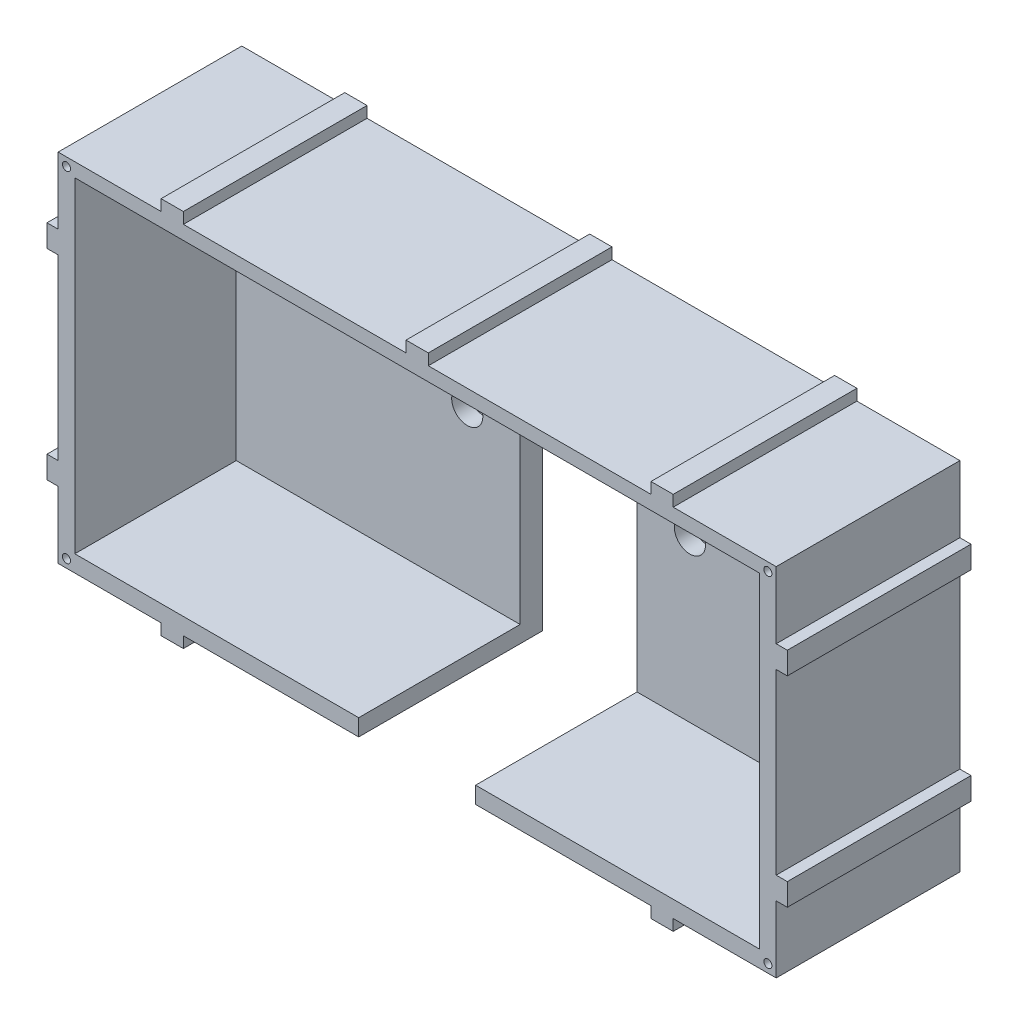
SolidWorks part; units mm, degrees
ref_plane "前视基准面" through (0, 0, 0) normal (0, 0, 1) x (1, 0, 0)
ref_plane "上视基准面" through (0, 0, 0) normal (0, 1, 0) x (1, 0, 0)
ref_plane "右视基准面" through (0, 0, 0) normal (1, 0, 0) x (0, 0, -1)
sketch "Model" plane through (0, 0, 0) normal (0, 0, 1) x (1, 0, 0)
  line L0 (257.5557, 185.1803) -> (276.0557, 185.1803)
  line L1 (386.5557, 121.1803) -> (368.0557, 121.1803)
  line L2 (257.5557, 121.1803) -> (257.5557, 133.1803)
  line L3 (386.5557, 185.1803) -> (386.5557, 173.1803)
  line L4 (324.0557, 185.1803) -> (324.0557, 187.1803)
  line L5 (324.0557, 187.1803) -> (320.0557, 187.1803)
  line L6 (320.0557, 187.1803) -> (320.0557, 185.1803)
  line L7 (280.0557, 185.1803) -> (280.0557, 187.1803)
  line L8 (280.0557, 187.1803) -> (276.0557, 187.1803)
  line L9 (276.0557, 187.1803) -> (276.0557, 185.1803)
  line L10 (368.0557, 185.1803) -> (368.0557, 187.1803)
  line L11 (368.0557, 187.1803) -> (364.0557, 187.1803)
  line L12 (364.0557, 187.1803) -> (364.0557, 185.1803)
  line L13 (280.0557, 121.1803) -> (280.0557, 119.1803)
  line L14 (280.0557, 119.1803) -> (276.0557, 119.1803)
  line L15 (276.0557, 119.1803) -> (276.0557, 121.1803)
  line L16 (368.0557, 121.1803) -> (368.0557, 119.1803)
  line L17 (368.0557, 119.1803) -> (364.0557, 119.1803)
  line L18 (364.0557, 119.1803) -> (364.0557, 121.1803)
  line L19 (257.5557, 173.1803) -> (255.5557, 173.1803)
  line L20 (255.5557, 173.1803) -> (255.5557, 169.1803)
  line L21 (255.5557, 169.1803) -> (257.5557, 169.1803)
  line L22 (257.5557, 133.1803) -> (255.5557, 133.1803)
  line L23 (255.5557, 133.1803) -> (255.5557, 137.1803)
  line L24 (255.5557, 137.1803) -> (257.5557, 137.1803)
  line L25 (386.5557, 173.1803) -> (388.5557, 173.1803)
  line L26 (388.5557, 173.1803) -> (388.5557, 169.1803)
  line L27 (388.5557, 169.1803) -> (386.5557, 169.1803)
  line L28 (386.5557, 133.1803) -> (388.5557, 133.1803)
  line L29 (388.5557, 133.1803) -> (388.5557, 137.1803)
  line L30 (388.5557, 137.1803) -> (386.5557, 137.1803)
  line L31 (257.5557, 173.1803) -> (257.5557, 185.1803)
  line L32 (257.5557, 137.1803) -> (257.5557, 169.1803)
  line L33 (276.0557, 121.1803) -> (257.5557, 121.1803)
  line L34 (364.0557, 121.1803) -> (332.5557, 121.1803)
  line L35 (386.5557, 133.1803) -> (386.5557, 121.1803)
  line L36 (386.5557, 169.1803) -> (386.5557, 137.1803)
  line L37 (368.0557, 185.1803) -> (386.5557, 185.1803)
  line L38 (332.5557, 121.1803) -> (332.5557, 182.6803)
  line L39 (311.5557, 121.1803) -> (311.5557, 182.6803)
  line L40 (311.5557, 182.6803) -> (332.5557, 182.6803)
  line L41 (311.5557, 121.1803) -> (280.0557, 121.1803)
  line L42 (280.0557, 185.1803) -> (320.0557, 185.1803)
  line L43 (324.0557, 185.1803) -> (364.0557, 185.1803)
  line L44 (322.0557, 182.6803) -> (322.0557, 130.4829) construction
  circle A0 centre (342.0557, 153.1803) radius 1.6
  circle A1 centre (302.0557, 153.1803) radius 1.6
extrude "凸台-拉伸1" add sketch "Model" along normal blind 4
sketch "草图2" plane through (0, 0, 4) normal (0, 0, 1) x (1, 0, 0)
  circle A0 centre (302.0557, 153.1803) radius 2.8
  circle A1 centre (342.0557, 153.1803) radius 2.8
  circle A2 centre (342.0557, 153.1803) radius 1.6 construction
  circle A3 centre (302.0557, 153.1803) radius 1.6 construction
  circle A4 centre (342.0557, 153.1803) radius 1.6
  circle A5 centre (302.0557, 153.1803) radius 1.6
  dimension "D1" = 5.6
  dimension "D2" = 5.6
extrude "切除-拉伸1" cut sketch "草图2" against normal blind 3
sketch "草图3" plane through (0, 0, 4) normal (0, 0, 1) x (1, 0, 0)
  line L0 (260.5557, 182.6803) -> (260.5557, 124.1803)
  line L1 (260.5557, 124.1803) -> (311.5557, 124.1803)
  line L2 (383.5557, 124.1803) -> (383.5557, 182.6803)
  line L4 (332.5557, 124.1803) -> (383.5557, 124.1803)
  line L5 (260.5557, 182.6803) -> (383.5557, 182.6803)
  line L44 (257.5557, 185.1803) -> (257.5557, 173.1803)
  line L45 (257.5557, 173.1803) -> (255.5557, 173.1803)
  line L46 (255.5557, 173.1803) -> (255.5557, 169.1803)
  line L47 (255.5557, 169.1803) -> (257.5557, 169.1803)
  line L48 (257.5557, 169.1803) -> (257.5557, 137.1803)
  line L49 (257.5557, 137.1803) -> (255.5557, 137.1803)
  line L50 (255.5557, 137.1803) -> (255.5557, 133.1803)
  line L51 (255.5557, 133.1803) -> (257.5557, 133.1803)
  line L52 (257.5557, 133.1803) -> (257.5557, 121.1803)
  line L53 (257.5557, 121.1803) -> (276.0557, 121.1803)
  line L54 (276.0557, 121.1803) -> (276.0557, 119.1803)
  line L55 (276.0557, 119.1803) -> (280.0557, 119.1803)
  line L56 (280.0557, 119.1803) -> (280.0557, 121.1803)
  line L57 (280.0557, 121.1803) -> (311.5557, 121.1803)
  line L58 (311.5557, 121.1803) -> (311.5557, 182.6803)
  line L59 (311.5557, 182.6803) -> (332.5557, 182.6803)
  line L60 (332.5557, 182.6803) -> (332.5557, 121.1803)
  line L61 (332.5557, 121.1803) -> (364.0557, 121.1803)
  line L62 (364.0557, 121.1803) -> (364.0557, 119.1803)
  line L63 (364.0557, 119.1803) -> (368.0557, 119.1803)
  line L64 (368.0557, 119.1803) -> (368.0557, 121.1803)
  line L65 (368.0557, 121.1803) -> (386.5557, 121.1803)
  line L66 (386.5557, 121.1803) -> (386.5557, 133.1803)
  line L67 (386.5557, 133.1803) -> (388.5557, 133.1803)
  line L68 (388.5557, 133.1803) -> (388.5557, 137.1803)
  line L69 (388.5557, 137.1803) -> (386.5557, 137.1803)
  line L70 (386.5557, 137.1803) -> (386.5557, 169.1803)
  line L71 (386.5557, 169.1803) -> (388.5557, 169.1803)
  line L72 (388.5557, 169.1803) -> (388.5557, 173.1803)
  line L73 (388.5557, 173.1803) -> (386.5557, 173.1803)
  line L74 (386.5557, 173.1803) -> (386.5557, 185.1803)
  line L75 (386.5557, 185.1803) -> (368.0557, 185.1803)
  line L76 (368.0557, 185.1803) -> (368.0557, 187.1803)
  line L77 (368.0557, 187.1803) -> (364.0557, 187.1803)
  line L78 (364.0557, 187.1803) -> (364.0557, 185.1803)
  line L79 (364.0557, 185.1803) -> (324.0557, 185.1803)
  line L80 (324.0557, 185.1803) -> (324.0557, 187.1803)
  line L81 (324.0557, 187.1803) -> (320.0557, 187.1803)
  line L82 (320.0557, 187.1803) -> (320.0557, 185.1803)
  line L83 (320.0557, 185.1803) -> (280.0557, 185.1803)
  line L84 (280.0557, 185.1803) -> (280.0557, 187.1803)
  line L85 (280.0557, 187.1803) -> (276.0557, 187.1803)
  line L86 (276.0557, 187.1803) -> (276.0557, 185.1803)
  line L87 (276.0557, 185.1803) -> (257.5557, 185.1803)
  line L88 (257.5557, 185.1803) -> (257.5557, 173.1803)
  line L89 (257.5557, 173.1803) -> (255.5557, 173.1803)
  line L90 (255.5557, 173.1803) -> (255.5557, 169.1803)
  line L91 (255.5557, 169.1803) -> (257.5557, 169.1803)
  line L92 (257.5557, 169.1803) -> (257.5557, 137.1803)
  line L93 (257.5557, 137.1803) -> (255.5557, 137.1803)
  line L94 (255.5557, 137.1803) -> (255.5557, 133.1803)
  line L95 (255.5557, 133.1803) -> (257.5557, 133.1803)
  line L96 (257.5557, 133.1803) -> (257.5557, 121.1803)
  line L97 (257.5557, 121.1803) -> (276.0557, 121.1803)
  line L98 (276.0557, 121.1803) -> (276.0557, 119.1803)
  line L99 (276.0557, 119.1803) -> (280.0557, 119.1803)
  line L100 (280.0557, 119.1803) -> (280.0557, 121.1803)
  line L101 (280.0557, 121.1803) -> (311.5557, 121.1803)
  line L102 (311.5557, 121.1803) -> (311.5557, 124.1803)
  line L104 (332.5557, 124.1803) -> (332.5557, 121.1803)
  line L105 (332.5557, 121.1803) -> (364.0557, 121.1803)
  line L106 (364.0557, 121.1803) -> (364.0557, 119.1803)
  line L107 (364.0557, 119.1803) -> (368.0557, 119.1803)
  line L108 (368.0557, 119.1803) -> (368.0557, 121.1803)
  line L109 (368.0557, 121.1803) -> (386.5557, 121.1803)
  line L110 (386.5557, 121.1803) -> (386.5557, 133.1803)
  line L111 (386.5557, 133.1803) -> (388.5557, 133.1803)
  line L112 (388.5557, 133.1803) -> (388.5557, 137.1803)
  line L113 (388.5557, 137.1803) -> (386.5557, 137.1803)
  line L114 (386.5557, 137.1803) -> (386.5557, 169.1803)
  line L115 (386.5557, 169.1803) -> (388.5557, 169.1803)
  line L116 (388.5557, 169.1803) -> (388.5557, 173.1803)
  line L117 (388.5557, 173.1803) -> (386.5557, 173.1803)
  line L118 (386.5557, 173.1803) -> (386.5557, 185.1803)
  line L119 (386.5557, 185.1803) -> (368.0557, 185.1803)
  line L120 (368.0557, 185.1803) -> (368.0557, 187.1803)
  line L121 (368.0557, 187.1803) -> (364.0557, 187.1803)
  line L122 (364.0557, 187.1803) -> (364.0557, 185.1803)
  line L123 (364.0557, 185.1803) -> (324.0557, 185.1803)
  line L124 (324.0557, 185.1803) -> (324.0557, 187.1803)
  line L125 (324.0557, 187.1803) -> (320.0557, 187.1803)
  line L126 (320.0557, 187.1803) -> (320.0557, 185.1803)
  line L127 (320.0557, 185.1803) -> (280.0557, 185.1803)
  line L128 (280.0557, 185.1803) -> (280.0557, 187.1803)
  line L129 (280.0557, 187.1803) -> (276.0557, 187.1803)
  line L130 (276.0557, 187.1803) -> (276.0557, 185.1803)
  line L131 (276.0557, 185.1803) -> (257.5557, 185.1803)
  dimension "D3" = 3
  dimension "D4" = 3
  dimension "D5" = 3
  dimension "D1" = 0
extrude "凸台-拉伸2" add sketch "草图3" along normal blind 29
sketch "草图6" plane through (0, 0, 33) normal (0, 0, 1) x (1, 0, 0)
  line L0 (276.0557, 185.1803) -> (257.5557, 185.1803) construction
  line L1 (386.5557, 185.1803) -> (368.0557, 185.1803) construction
  line L2 (257.5557, 185.1803) -> (257.5557, 173.1803) construction
  line L3 (386.5557, 173.1803) -> (386.5557, 185.1803) construction
  line L4 (386.5557, 121.1803) -> (386.5557, 133.1803) construction
  line L5 (368.0557, 121.1803) -> (386.5557, 121.1803) construction
  circle A0 centre (259.0557, 183.6803) radius 0.725
  circle A1 centre (385.0557, 183.6803) radius 0.725
  circle A2 centre (385.0557, 122.6803) radius 0.725
  circle A3 centre (259.0557, 122.6803) radius 0.725
  dimension "D1" = 1.45
  dimension "D4" = 1.45
  dimension "D7" = 1.45
  dimension "D10" = 1.45
  dimension "D2" = 1.5
  dimension "D3" = 1.5
  dimension "D5" = 1.5
  dimension "D6" = 1.5
  dimension "D8" = 1.5
  dimension "D9" = 1.5
extrude "切除-拉伸2" cut sketch "草图6" against normal blind 7
